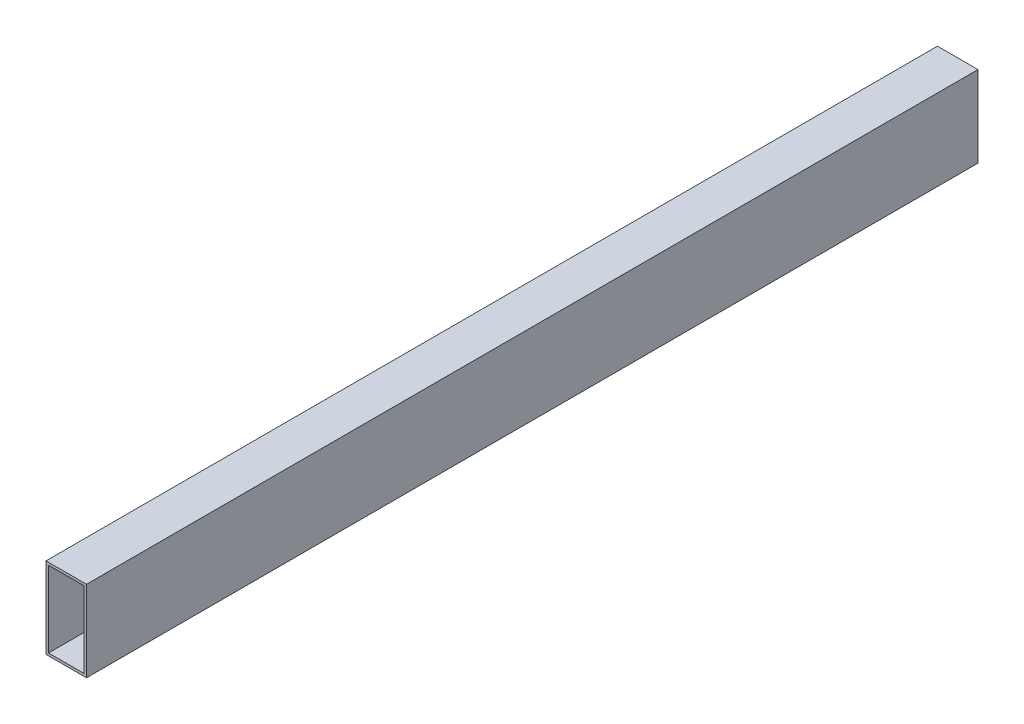
SolidWorks part; units mm, degrees
ref_plane "Front Plane" through (0, 0, 0) normal (0, 0, 1) x (1, 0, 0)
ref_plane "Top Plane" through (0, 0, 0) normal (0, 1, 0) x (1, 0, 0)
ref_plane "Right Plane" through (0, 0, 0) normal (1, 0, 0) x (0, 0, -1)
sketch "Sketch1" plane through (0, 0, 0) normal (0, 0, 1) x (1, 0, 0)
  line L0 (11.1125, -23.8125) -> (11.1125, 23.8125)
  line L1 (-12.7, -25.4) -> (12.7, -25.4)
  line L2 (-12.7, -25.4) -> (-12.7, 25.4)
  line L3 (-12.7, 25.4) -> (12.7, 25.4)
  line L4 (12.7, -25.4) -> (12.7, 25.4)
  line L5 (-12.7, -25.4) -> (12.7, 25.4) construction
  line L6 (-12.7, 25.4) -> (12.7, -25.4) construction
  line L7 (-11.1125, 23.8125) -> (11.1125, 23.8125)
  line L8 (-11.1125, -23.8125) -> (-11.1125, 23.8125)
  line L9 (-11.1125, -23.8125) -> (11.1125, -23.8125)
  point P0 (0, 0)
  dimension "D1" = 25.4
  dimension "D2" = 50.8
  dimension "D3" = 1.5875
extrude "Boss-Extrude1" add sketch "Sketch1" along normal mid plane 558.8
